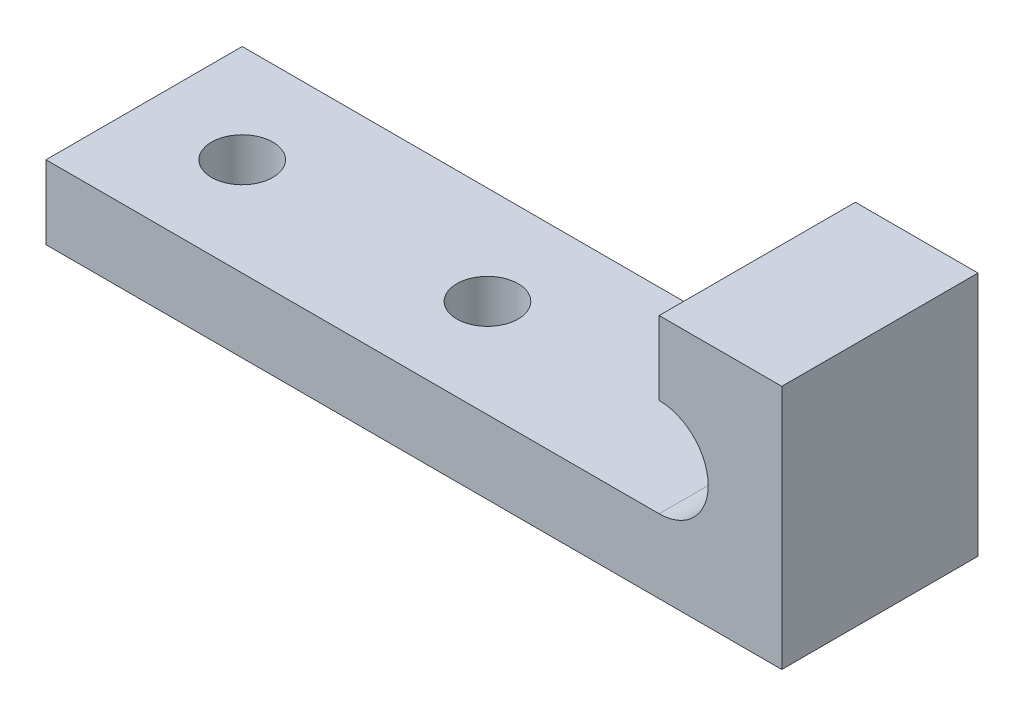
SolidWorks part; units mm, degrees
ref_plane "Front Plane" through (0, 0, 0) normal (0, 0, 1) x (1, 0, 0)
ref_plane "Top Plane" through (0, 0, 0) normal (0, 1, 0) x (1, 0, 0)
ref_plane "Right Plane" through (0, 0, 0) normal (1, 0, 0) x (0, 0, -1)
sketch "Sketch1" plane through (0, 0, 0) normal (0, 0, 1) x (1, 0, 0)
  line L0 (-68.4007, 33.4609) -> (-48.4007, 33.4609)
  line L1 (-48.4007, 33.4609) -> (-48.4007, 23.4609)
  line L2 (-48.4007, 23.4609) -> (-68.4007, 23.4609)
  line L3 (-68.4007, 23.4609) -> (-68.4007, 33.4609)
extrude "Boss-Extrude1" add sketch "Sketch1" along normal blind 8
sketch "Sketch2" plane through (0, 0, 8) normal (0, 0, 1) x (1, 0, 0)
  line L1 (-48.4007, 33.4609) -> (-68.4007, 33.4609) construction
  line L2 (-53.4007, 33.4609) -> (-53.4007, 30.4609)
  line L3 (-53.4007, 26.4609) -> (-68.4007, 26.4609)
  line L4 (-68.4007, 33.4609) -> (-68.4007, 23.4609) construction
  line L5 (-68.4007, 26.4609) -> (-68.4007, 33.4609)
  line L6 (-68.4007, 33.4609) -> (-53.4007, 33.4609)
  arc A0 (-53.4007, 26.4609) -> (-53.4007, 30.4609) centre (-53.4007, 28.4609) ccw
extrude "Cut-Extrude2" cut sketch "Sketch2" against normal blind 8
sketch "Sketch3" plane through (0, 0, 8) normal (0, 0, 1) x (1, 0, 0)
  line L0 (-68.4007, 26.4609) -> (-78.4007, 26.4609)
  line L1 (-78.4007, 26.4609) -> (-78.4007, 23.4609)
  line L2 (-78.4007, 23.4609) -> (-68.4007, 23.4609)
  line L3 (-68.4007, 23.4609) -> (-68.4007, 26.4609)
extrude "Boss-Extrude2" add sketch "Sketch3" against normal blind 8
sketch "Sketch4" plane through (0, 26.4609, 0) normal (0, 1, 0) x (1, 0, 0)
  circle A0 centre (-74.4007, -4) radius 1.25
extrude "Cut-Extrude3" cut sketch "Sketch4" against normal blind 8
sketch "Sketch5" plane through (0, 26.4609, 0) normal (0, 1, 0) x (1, 0, 0)
  circle A0 centre (-64.4007, -4) radius 1.25
extrude "Cut-Extrude4" cut sketch "Sketch5" against normal blind 8
